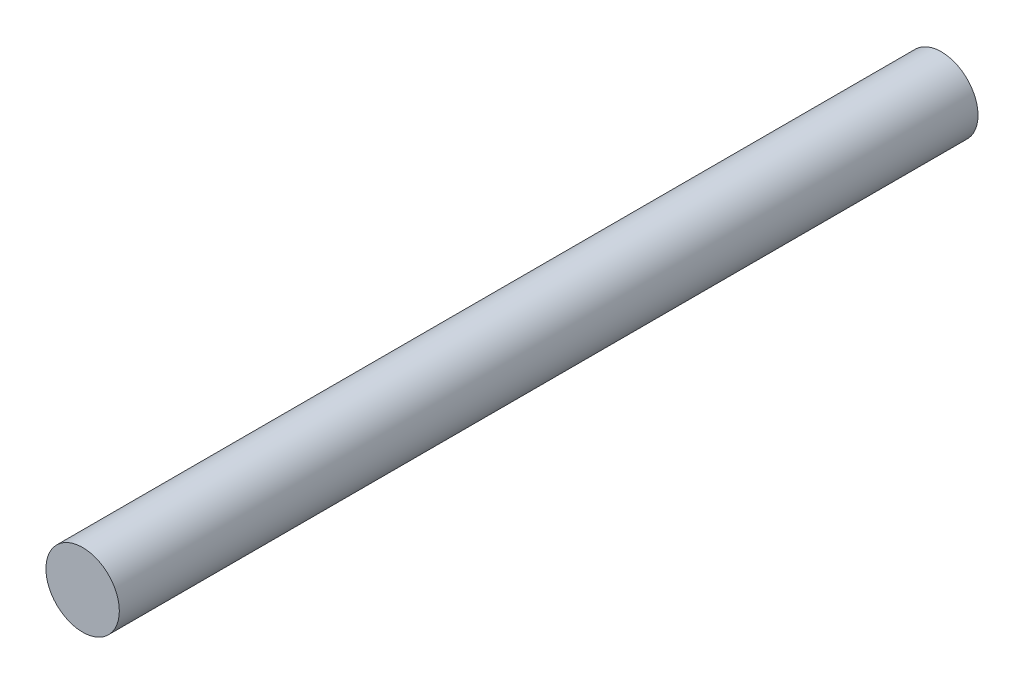
SolidWorks part; units mm, degrees
ref_plane "前视基准面" through (0, 0, 0) normal (0, 0, 1) x (1, 0, 0)
ref_plane "上视基准面" through (0, 0, 0) normal (0, 1, 0) x (1, 0, 0)
ref_plane "右视基准面" through (0, 0, 0) normal (1, 0, 0) x (0, 0, -1)
other "Configuration Table"
sketch "草图1" plane through (0, 0, 0) normal (0, 0, 1) x (1, 0, 0)
  circle A0 centre (0, 0) radius 2
extrude "轴向尺寸_46.8" add sketch "草图1" along normal blind 46.8
